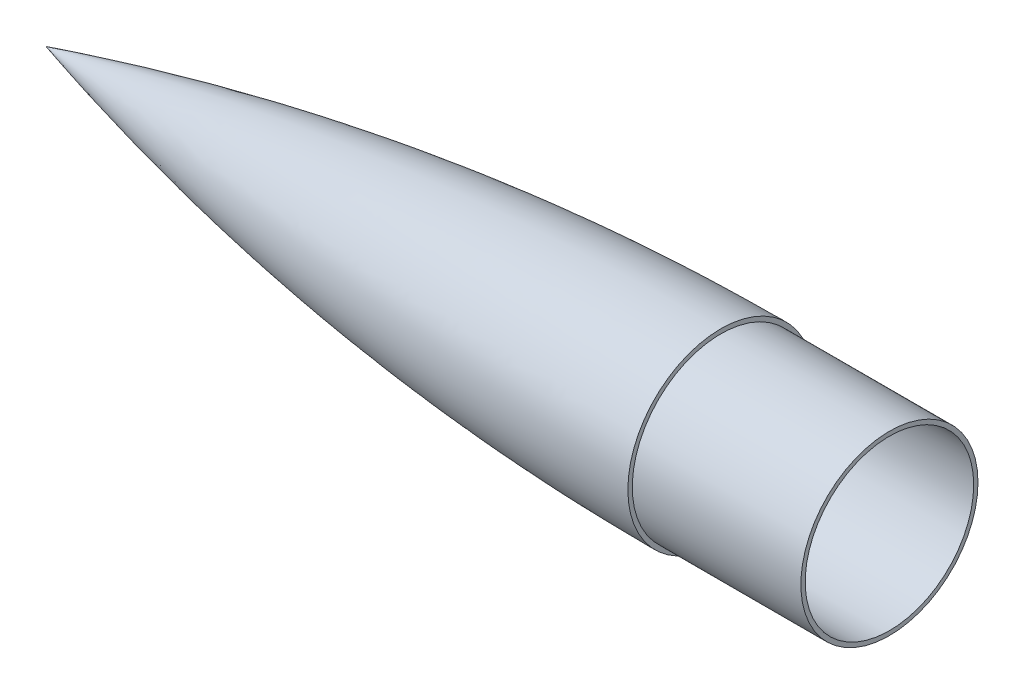
SolidWorks part; units mm, degrees
ref_plane "Front Plane" through (0, 0, 0) normal (0, 0, 1) x (1, 0, 0)
ref_plane "Top Plane" through (0, 0, 0) normal (0, 1, 0) x (1, 0, 0)
ref_plane "Right Plane" through (0, 0, 0) normal (1, 0, 0) x (0, 0, -1)
sketch "Sketch6" plane through (0, 0, 0) normal (0, 0, 1) x (1, 0, 0)
  line L0 (0, 0.0008) -> (285.75, 0.0008)
  line L1 (285.75, 0.0008) -> (285.75, 39.37)
  spline S0 degree 4 poles (-27.718, -8.1953) (-27.5001, -8.1277) (-27.0654, -7.9928) (-26.2032, -7.7256) (-24.4536, -7.1863) (-22.0873, -6.4611) (-19.0073, -5.5284) (-15.5867, -4.5034) (-12.0456, -3.4578) (-8.7141, -2.4838) (-5.4858, -1.5549) (-3.2254, -0.9089) (-0.5524, -0.1541) (0.4894, 0.1385) (2.6588, 0.7449) (4.0536, 1.1308) (5.8591, 1.6292) (7.4449, 2.063) (9.5611, 2.6392) (12.0317, 3.3054) (14.9586, 4.0867) (18.2813, 4.9617) (21.6195, 5.8294) (25.7881, 6.8982) (30.8004, 8.1603) (35.8167, 9.3943) (40.8413, 10.6016) (45.8703, 11.7868) (50.9048, 12.9502) (56.7854, 14.2755) (65.1987, 16.1141) (73.6276, 17.8794) (82.0716, 19.5715) (92.2215, 21.5137) (109.1657, 24.6037) (127.8692, 27.6377) (146.6343, 30.2646) (163.735, 32.3184) (174.0057, 33.4615) (184.286, 34.5152) (194.5773, 35.4572) (204.8781, 36.2872) (213.4678, 36.9043) (220.3424, 37.3531) (227.2201, 37.7572) (233.2399, 38.0714) (238.4017, 38.3128) (242.703, 38.4952) (246.1464, 38.6299) (249.5862, 38.7534) (253.0336, 38.8657) (256.4692, 38.9667) (259.9254, 39.0565) (263.3482, 39.1351) (266.8269, 39.2025) (270.2131, 39.2586) (273.7577, 39.3036) (276.6063, 39.333) (279.4407, 39.3513) (281.5988, 39.3639) (285.153, 39.371) (286.4237, 39.3709) (289.9974, 39.3635) (293.1107, 39.3456) (296.9959, 39.3157) (300.7833, 39.2662) (305.3931, 39.1909) (308.4504, 39.1272) (311.2062, 39.065) (312.9646, 39.0195) (313.8801, 38.9957) (314.3264, 38.9836) knots 0 0 0 0 0 0.00262 0.00524 0.01048 0.02096 0.03144 0.041921 0.052275 0.06263 0.072985 0.078162 0.083339 0.088305 0.093271 0.098237 0.103203 0.108168 0.113134 0.123066 0.132998 0.142929 0.152861 0.162793 0.182656 0.20252 0.212451 0.222383 0.242246 0.26211 0.281973 0.3217 0.341563 0.361427 0.401154 0.520334 0.560061 0.579924 0.599788 0.639515 0.679241 0.699105 0.718968 0.738832 0.758695 0.778558 0.78849 0.798422 0.808354 0.818285 0.828217 0.838149 0.84808 0.858012 0.867944 0.877875 0.887807 0.897739 0.902705 0.907671 0.917602 0.927839 0.932958 0.938076 0.95855 0.968912 0.979275 0.989637 0.994819 1 1 1 1 1 construction
  spline S1 degree 4 poles (0, 0.0008) (0.3458, 0.0979) (1.0489, 0.2949) (2.6588, 0.7449) (4.0536, 1.1308) (5.8591, 1.6292) (7.4449, 2.063) (9.5611, 2.6392) (12.0317, 3.3054) (14.9586, 4.0867) (18.2813, 4.9617) (21.6195, 5.8294) (25.7881, 6.8982) (30.8004, 8.1603) (35.8167, 9.3943) (40.8413, 10.6016) (45.8703, 11.7868) (50.9048, 12.9502) (56.7854, 14.2755) (65.1987, 16.1141) (73.6276, 17.8794) (82.0716, 19.5715) (92.2215, 21.5137) (109.1657, 24.6037) (127.8692, 27.6377) (146.6343, 30.2646) (163.735, 32.3184) (174.0057, 33.4615) (184.286, 34.5152) (194.5773, 35.4572) (204.8781, 36.2872) (213.4678, 36.9043) (220.3424, 37.3531) (227.2201, 37.7572) (233.2399, 38.0714) (238.4017, 38.3128) (242.703, 38.4952) (246.1464, 38.6299) (249.5862, 38.7534) (253.0336, 38.8657) (256.4692, 38.9667) (259.9254, 39.0565) (263.3482, 39.1351) (266.8269, 39.2025) (270.2131, 39.2586) (273.7577, 39.3036) (276.6063, 39.333) (279.4407, 39.3513) (281.5988, 39.3639) (283.9442, 39.3686) (285.0316, 39.37) (285.75, 39.37) knots 0.083339 0.083339 0.083339 0.083339 0.083339 0.088305 0.093271 0.098237 0.103203 0.108168 0.113134 0.123066 0.132998 0.142929 0.152861 0.162793 0.182656 0.20252 0.212451 0.222383 0.242246 0.26211 0.281973 0.3217 0.341563 0.361427 0.401154 0.520334 0.560061 0.579924 0.599788 0.639515 0.679241 0.699105 0.718968 0.738832 0.758695 0.778558 0.78849 0.798422 0.808354 0.818285 0.828217 0.838149 0.84808 0.858012 0.867944 0.877875 0.887807 0.897739 0.902705 0.907671 0.917602 0.917602 0.917602 0.917602 0.917602
  spline S2 degree 4 poles (-27.718, -10.1553) (-27.5001, -10.0877) (-27.0654, -9.9528) (-26.2032, -9.6856) (-24.4536, -9.1463) (-22.0873, -8.4211) (-19.0073, -7.4884) (-15.5867, -6.4634) (-12.0456, -5.4178) (-8.7141, -4.4438) (-5.4858, -3.5149) (-3.2254, -2.8689) (-0.5524, -2.1141) (0.4894, -1.8215) (2.6588, -1.2151) (4.0536, -0.8292) (5.8591, -0.3308) (7.4449, 0.103) (9.5611, 0.6792) (12.0317, 1.3454) (14.9586, 2.1267) (18.2813, 3.0017) (21.6195, 3.8694) (25.7881, 4.9382) (30.8004, 6.2003) (35.8167, 7.4343) (40.8413, 8.6416) (45.8703, 9.8268) (50.9048, 10.9902) (56.7854, 12.3155) (65.1987, 14.1541) (73.6276, 15.9194) (82.0716, 17.6115) (92.2215, 19.5537) (109.1657, 22.6437) (127.8692, 25.6777) (146.6343, 28.3046) (163.735, 30.3584) (174.0057, 31.5015) (184.286, 32.5552) (194.5773, 33.4972) (204.8781, 34.3272) (213.4678, 34.9443) (220.3424, 35.3931) (227.2201, 35.7972) (233.2399, 36.1114) (238.4017, 36.3528) (242.703, 36.5352) (246.1464, 36.6699) (249.5862, 36.7934) (253.0336, 36.9057) (256.4692, 37.0067) (259.9254, 37.0965) (263.3482, 37.1751) (266.8269, 37.2425) (270.2131, 37.2986) (273.7577, 37.3436) (276.6063, 37.373) (279.4407, 37.3913) (281.5988, 37.4039) (285.153, 37.411) (286.4237, 37.4109) (289.9974, 37.4035) (293.1107, 37.3856) (296.9959, 37.3557) (300.7833, 37.3062) (305.3931, 37.2309) (308.4504, 37.1672) (311.2062, 37.105) (312.9646, 37.0595) (313.8801, 37.0357) (314.3264, 37.0236) knots 0 0 0 0 0 0.00262 0.00524 0.01048 0.02096 0.03144 0.041921 0.052275 0.06263 0.072985 0.078162 0.083339 0.088305 0.093271 0.098237 0.103203 0.108168 0.113134 0.123066 0.132998 0.142929 0.152861 0.162793 0.182656 0.20252 0.212451 0.222383 0.242246 0.26211 0.281973 0.3217 0.341563 0.361427 0.401154 0.520334 0.560061 0.579924 0.599788 0.639515 0.679241 0.699105 0.718968 0.738832 0.758695 0.778558 0.78849 0.798422 0.808354 0.818285 0.828217 0.838149 0.84808 0.858012 0.867944 0.877875 0.887807 0.897739 0.902705 0.907671 0.917602 0.927839 0.932958 0.938076 0.95855 0.968912 0.979275 0.989637 0.994819 1 1 1 1 1 construction
  spline S3 degree 4 poles (7.0722, 0.0008) (7.3749, 0.0835) (8.0878, 0.278) (9.668, 0.708) (12.0317, 1.3454) (14.9586, 2.1267) (18.2813, 3.0017) (21.6195, 3.8694) (25.7881, 4.9382) (30.8004, 6.2003) (35.8167, 7.4343) (40.8413, 8.6416) (45.8703, 9.8268) (50.9048, 10.9902) (56.7854, 12.3155) (65.1987, 14.1541) (73.6276, 15.9194) (82.0716, 17.6115) (92.2215, 19.5537) (109.1657, 22.6437) (127.8692, 25.6777) (146.6343, 28.3046) (163.735, 30.3584) (174.0057, 31.5015) (184.286, 32.5552) (194.5773, 33.4972) (204.8781, 34.3272) (213.4678, 34.9443) (220.3424, 35.3931) (227.2201, 35.7972) (233.2399, 36.1114) (238.4017, 36.3528) (242.703, 36.5352) (246.1464, 36.6699) (249.5862, 36.7934) (253.0336, 36.9057) (256.4692, 37.0067) (259.9254, 37.0965) (263.3482, 37.1751) (266.8269, 37.2425) (270.2131, 37.2986) (273.7577, 37.3436) (276.6063, 37.373) (279.4407, 37.3913) (281.5988, 37.4039) (283.9442, 37.4086) (285.0316, 37.41) (285.75, 37.41) knots 0.104492 0.104492 0.104492 0.104492 0.104492 0.108168 0.113134 0.123066 0.132998 0.142929 0.152861 0.162793 0.182656 0.20252 0.212451 0.222383 0.242246 0.26211 0.281973 0.3217 0.341563 0.361427 0.401154 0.520334 0.560061 0.579924 0.599788 0.639515 0.679241 0.699105 0.718968 0.738832 0.758695 0.778558 0.78849 0.798422 0.808354 0.818285 0.828217 0.838149 0.84808 0.858012 0.867944 0.877875 0.887807 0.897739 0.902705 0.907671 0.917602 0.917602 0.917602 0.917602 0.917602
  dimension "D1" = 1.96
revolve "Revolve1" add sketch "Sketch6" angle 360 about L0
sketch "Sketch7" plane through (285.75, 0, 0) normal (1, 0, 0) x (0, 0, -1)
  circle A0 centre (0, 0) radius 35.68
  circle A1 centre (0, 0) radius 37.5
  dimension "D1" = 75
  dimension "D2" = 71.36
extrude "Boss-Extrude2" add sketch "Sketch7" along normal blind 71.4 and the other way blind 10
